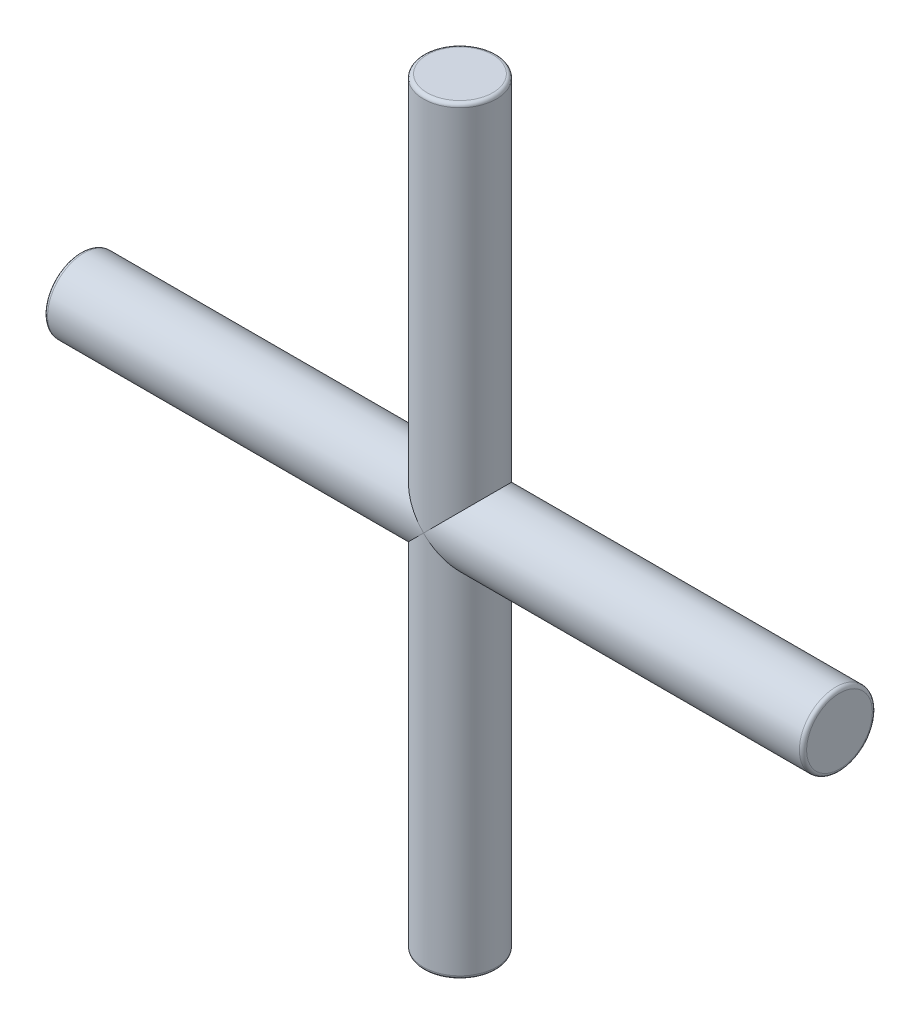
SolidWorks part; units mm, degrees
ref_plane "Front Plane" through (0, 0, 0) normal (0, 0, 1) x (1, 0, 0)
ref_plane "Top Plane" through (0, 0, 0) normal (0, 1, 0) x (1, 0, 0)
ref_plane "Right Plane" through (0, 0, 0) normal (1, 0, 0) x (0, 0, -1)
sketch "Sketch1" plane through (0, 0, 0) normal (1, 0, 0) x (0, 0, -1)
  circle A0 centre (0, 0) radius 2500
  dimension "D1" = 5000
extrude "Boss-Extrude1" add sketch "Sketch1" along normal mid plane 52000
sketch "Sketch3" plane through (0, 0, 0) normal (0, 1, 0) x (1, 0, 0)
  circle A0 centre (0, 0) radius 2500
  dimension "D1" = 5000
extrude "Boss-Extrude2" add sketch "Sketch3" along normal mid plane 52000
fillet "Fillet1" radius 250 4 edges at (26000, 0, -2500) (-26000, 0, -2500) (0, -26000, 2500) (0, 26000, 2500)
